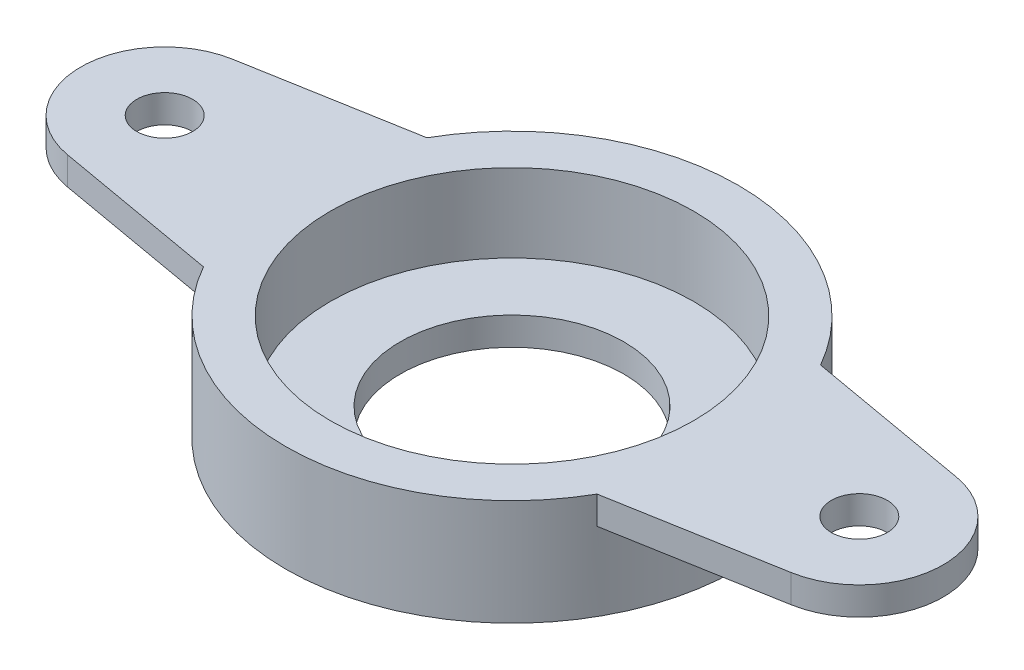
SolidWorks part; units mm, degrees
ref_plane "Front Plane" through (0, 0, 0) normal (0, 0, 1) x (1, 0, 0)
ref_plane "Top Plane" through (0, 0, 0) normal (0, 1, 0) x (1, 0, 0)
ref_plane "Right Plane" through (0, 0, 0) normal (1, 0, 0) x (0, 0, -1)
sketch "Sketch1" plane through (0, 0, 0) normal (0, 1, 0) x (1, 0, 0)
  circle A0 centre (0, 0) radius 25.7175
  circle A1 centre (0, 0) radius 20.6375
  dimension "D1" = 5.08
  dimension "D2" = 41.275
extrude "Boss-Extrude1" add sketch "Sketch1" along normal blind 8.89
sketch "Sketch2" plane through (0, 0, 0) normal (0, -1, 0) x (1, 0, 0)
  circle A0 centre (0, 0) radius 25.7175
  circle A1 centre (0, 0) radius 12.7
  circle A2 centre (0, 0) radius 25.7175 construction
  dimension "D1" = 25.4
extrude "Boss-Extrude2" add sketch "Sketch2" along normal blind 3.175
sketch "Sketch3" plane through (0, 8.89, 0) normal (0, 1, 0) x (1, 0, 0)
  line L0 (22.3629, 12.7) -> (41.1235, 9.392)
  line L1 (22.3629, -12.7) -> (41.1235, -9.392)
  line L2 (0, 0) -> (92.454, 0) construction
  line L3 (0, 0) -> (0, -34.0997) construction
  line L4 (-22.3629, -12.7) -> (-41.1235, -9.392)
  line L5 (-22.3629, 12.7) -> (-41.1235, 9.392)
  circle A0 centre (0, 0) radius 25.7175 construction
  circle A1 centre (0, 0) radius 25.7175 construction
  arc A2 (22.3629, 12.7) -> (22.3629, -12.7) centre (0, 0) cw
  arc A3 (41.1235, 9.392) -> (41.1235, -9.392) centre (39.4674, 0) cw
  circle A4 centre (39.4674, 0) radius 3.175
  circle A5 centre (-39.4674, 0) radius 3.175
  arc A6 (-41.1235, 9.392) -> (-41.1235, -9.392) centre (-39.4674, 0) ccw
  arc A7 (-22.3629, 12.7) -> (-22.3629, -12.7) centre (0, 0) ccw
  dimension "D6" = 6.35
  dimension "D1" = 10
  dimension "D2" = 10
  dimension "D3" = 19.05
  dimension "D4" = 12.7
  dimension "D5" = 12.7
extrude "Boss-Extrude3" add sketch "Sketch3" against normal blind 3.175
equation "\"D2@Sketch3\"=\"D1@Sketch3\""
equation "\"D5@Sketch3\"=\"D4@Sketch3\""
